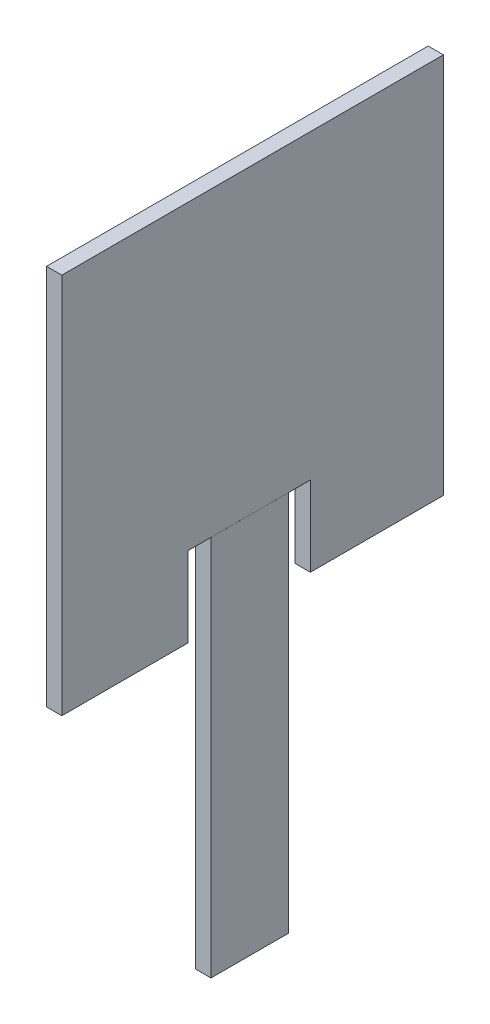
SolidWorks part; units mm, degrees
ref_plane "Front Plane" through (0, 0, 0) normal (0, 0, 1) x (1, 0, 0)
ref_plane "Top Plane" through (0, 0, 0) normal (0, 1, 0) x (1, 0, 0)
ref_plane "Right Plane" through (0, 0, 0) normal (1, 0, 0) x (0, 0, -1)
sketch "Sketch1" plane through (0, 0, 0) normal (1, 0, 0) x (0, 0, -1)
  line L1 (-1.25, 1.25) -> (1.25, 1.25)
  line L2 (-1.25, 1.25) -> (-1.25, -1.25)
  line L3 (-1.25, -1.25) -> (1.25, -1.25)
  line L4 (1.25, 1.25) -> (1.25, -1.25)
  line L5 (-1.25, 1.25) -> (1.25, -1.25) construction
  line L6 (-1.25, -1.25) -> (1.25, 1.25) construction
  point P0 (0, 0)
  dimension "D1" = 2.5
  dimension "D2" = 2.5
extrude "Boss-Extrude1" add sketch "Sketch1" along normal blind 0.1
sketch "Sketch3" plane through (0.1, 0, 0) normal (1, 0, 0) x (0, 0, -1)
  line L1 (-0.4219, -1.644) -> (0.3781, -1.644)
  line L2 (-0.4219, -1.644) -> (-0.4219, -0.7263)
  line L3 (-0.4219, -0.7263) -> (0.3781, -0.7263)
  line L4 (0.3781, -1.644) -> (0.3781, -0.7263)
  line L5 (-0.4219, -1.644) -> (0.3781, -0.7263) construction
  line L6 (-0.4219, -0.7263) -> (0.3781, -1.644) construction
  point P0 (-0.0219, -1.1851)
  dimension "D1" = 0.8
extrude "Cut-Extrude3" cut sketch "Sketch3" against normal blind 10
sketch "Sketch4" plane through (0, -0.7263, 0) normal (0, -1, 0) x (-1, 0, 0)
  line L0 (0, 0.3781) -> (0, -0.4219) construction
  line L1 (-0.1, -0.2729) -> (0, -0.2729)
  line L2 (-0.1, -0.2729) -> (-0.1, 0.234)
  line L3 (-0.1, 0.234) -> (0, 0.234)
  line L4 (0, -0.2729) -> (0, 0.234)
  line L5 (-0.1, -0.2729) -> (0, 0.234) construction
  line L6 (-0.1, 0.234) -> (0, -0.2729) construction
  point P0 (-0.05, -0.0194)
extrude "Boss-Extrude3" add sketch "Sketch4" along normal blind 2.5
